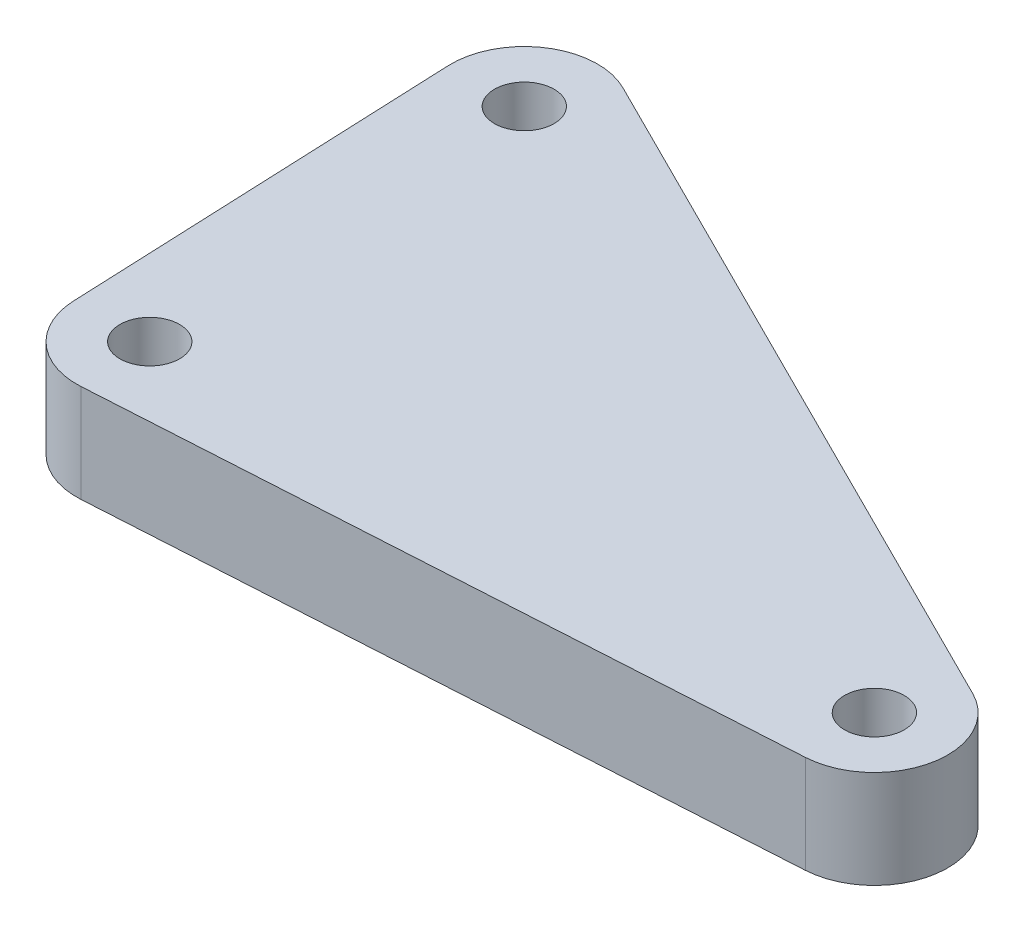
SolidWorks part; units mm, degrees
material "ABS"
ref_plane "Front Plane" through (0, 0, 0) normal (0, 0, 1) x (1, 0, 0)
ref_plane "Top Plane" through (0, 0, 0) normal (0, 1, 0) x (1, 0, 0)
ref_plane "Right Plane" through (0, 0, 0) normal (1, 0, 0) x (0, 0, -1)
sketch "Sketch1" plane through (0, 0, 0) normal (0, 1, 0) x (1, 0, 0)
  line L0 (0, 0) -> (-71.5567, 35.7719) construction
  line L2 (3.3536, 6.7084) -> (-68.2031, 42.4804)
  line L3 (-71.5567, 35.7719) -> (-69.8743, -4.1927) construction
  line L5 (-79.0501, 35.4565) -> (-77.3677, -4.5081)
  line L6 (-69.8743, -4.1927) -> (0, 0) construction
  line L8 (-69.4251, -11.6792) -> (0.4492, -7.4865)
  line L10 (-62.3866, -3.7434) -> (-62.381, -3.8772)
  arc A2 (-68.2031, 42.4804) -> (-79.0501, 35.4565) centre (-71.5567, 35.7719) ccw
  arc A4 (-77.3677, -4.5081) -> (-69.4251, -11.6792) centre (-69.8743, -4.1927) ccw
  arc A5 (0.4492, -7.4865) -> (3.3536, 6.7084) centre (0, 0) ccw
  circle A6 centre (-71.5567, 35.7719) radius 3.05
  circle A7 centre (-69.8743, -4.1927) radius 3.05
  circle A8 centre (0, 0) radius 3.05
  point P3 (-35.7784, 17.886)
  point P8 (-70.7155, 15.7896)
  point P15 (-34.9372, -2.0963)
  dimension "D4" = 6.1
  dimension "D1" = 80
  dimension "D2" = 40
  dimension "D3" = 70
extrude "Boss-Extrude1" add sketch "Sketch1" along normal blind 10
